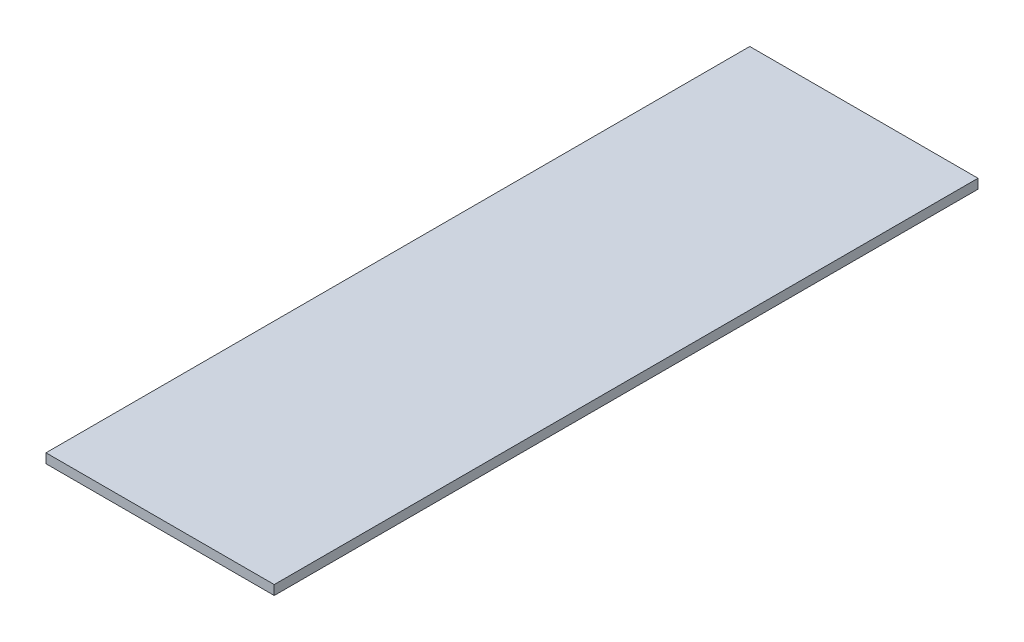
SolidWorks part; units mm, degrees
ref_plane "Front Plane" through (0, 0, 0) normal (0, 0, 1) x (1, 0, 0)
ref_plane "Top Plane" through (0, 0, 0) normal (0, 1, 0) x (1, 0, 0)
ref_plane "Right Plane" through (0, 0, 0) normal (1, 0, 0) x (0, 0, -1)
sketch "Sketch1" plane through (0, 0, 0) normal (0, 1, 0) x (1, 0, 0)
  line L1 (0, 0) -> (120, 0)
  line L2 (0, 0) -> (0, 370)
  line L3 (0, 370) -> (120, 370)
  line L4 (120, 0) -> (120, 370)
  dimension "D1" = 120
  dimension "D2" = 370
extrude "Boss-Extrude1" add sketch "Sketch1" along normal blind 5
